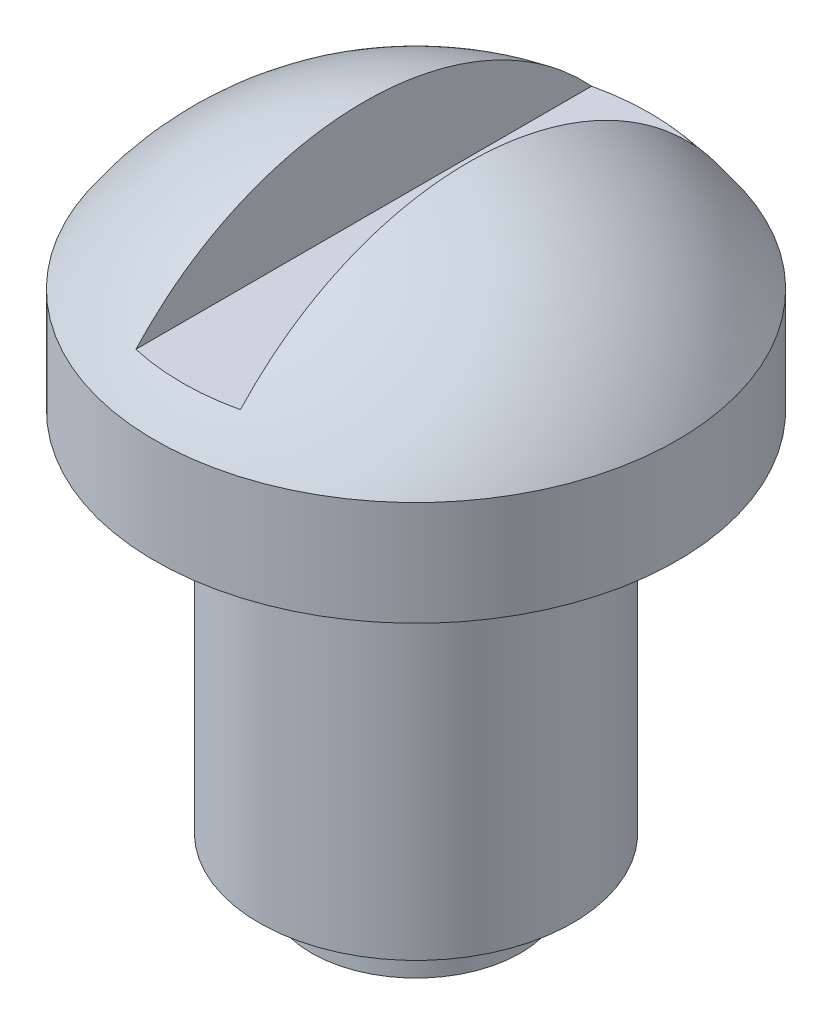
SolidWorks part; units mm, degrees
ref_plane "Front Plane" through (0, 0, 0) normal (0, 0, 1) x (1, 0, 0)
ref_plane "Top Plane" through (0, 0, 0) normal (0, 1, 0) x (1, 0, 0)
ref_plane "Right Plane" through (0, 0, 0) normal (1, 0, 0) x (0, 0, -1)
sketch "Sketch1" plane through (0, 0, 0) normal (0, 0, 1) x (1, 0, 0)
  line L0 (-2, 0) -> (0, 0) construction
  line L1 (2, 0) -> (2, 1)
  line L2 (-2, 0) -> (-2, 1) construction
  line L3 (0, 0) -> (2, 0)
  line L4 (-2, 1) -> (-3, 1) construction
  line L5 (2, 1) -> (3, 1)
  line L6 (-3, 1) -> (-3, 8) construction
  line L7 (3, 1) -> (3, 8)
  line L8 (3, 8) -> (5, 8)
  line L9 (-3, 8) -> (-5, 8) construction
  line L10 (5, 8) -> (5, 10)
  line L11 (-5, 8) -> (-5, 10) construction
  line L12 (0, 12.6834) -> (0, 0)
  arc A1 (-5, 10) -> (0, 12.6834) centre (0, 6.6834) cw construction
  arc A2 (0, 12.6834) -> (5, 10) centre (0, 6.6834) cw
  point P4 (0, 0)
  point P18 (0, 0)
  point P19 (0, 0)
  dimension "D7" = 6
  dimension "D1" = 4
  dimension "D2" = 1
  dimension "D3" = 6
  dimension "D4" = 7
  dimension "D5" = 10
  dimension "D6" = 2
revolve "Revolve1" add sketch "Sketch1" angle 360 about L12
sketch "Sketch2" plane through (0, 0, 0) normal (0, 0, 1) x (1, 0, 0)
  line L0 (-1, 12.6834) -> (1, 12.6834)
  line L1 (-1, 12.6834) -> (-1, 10.6834)
  line L2 (-1, 10.6834) -> (1, 10.6834)
  line L3 (1, 10.6834) -> (1, 12.6834)
  point P3 (0, 12.6834)
  point P5 (0, 0)
  dimension "D1" = 2
  dimension "D2" = 2
extrude "Cut-Extrude1" cut sketch "Sketch2" against normal through all and the other way through all
